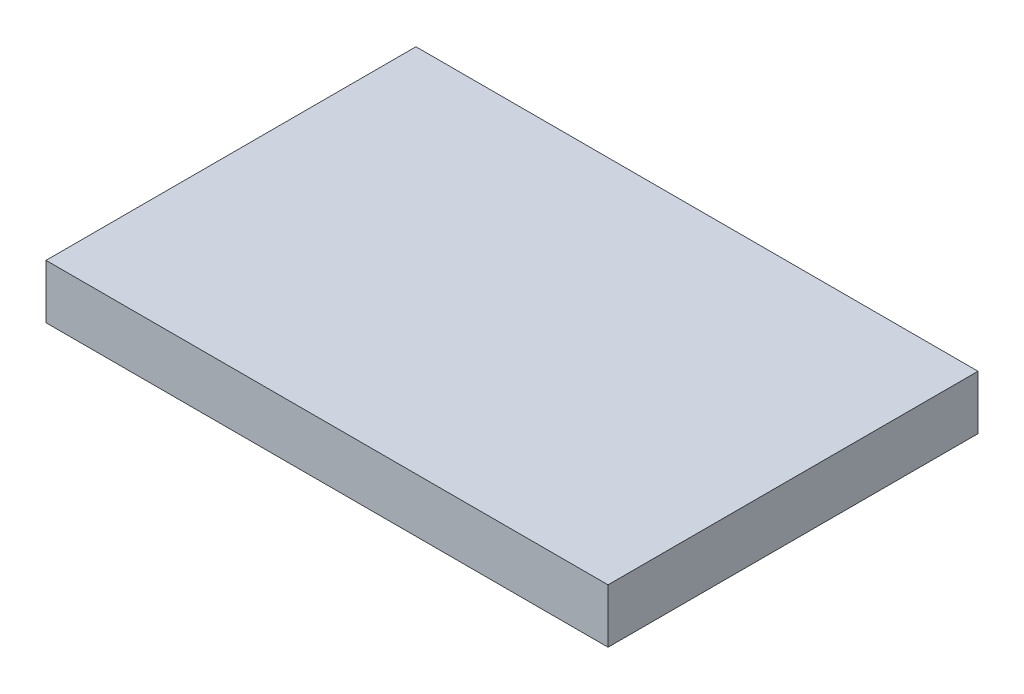
SolidWorks part; units mm, degrees
ref_plane "Front Plane" through (0, 0, 0) normal (0, 0, 1) x (1, 0, 0)
ref_plane "Top Plane" through (0, 0, 0) normal (0, 1, 0) x (1, 0, 0)
ref_plane "Right Plane" through (0, 0, 0) normal (1, 0, 0) x (0, 0, -1)
sketch "Sketch1" plane through (0, 0, 0) normal (0, 1, 0) x (1, 0, 0)
  line L1 (-197.5, 130) -> (197.5, 130)
  line L2 (-197.5, 130) -> (-197.5, -130)
  line L3 (-197.5, -130) -> (197.5, -130)
  line L4 (197.5, 130) -> (197.5, -130)
  line L5 (-197.5, 130) -> (197.5, -130) construction
  line L6 (-197.5, -130) -> (197.5, 130) construction
  point P0 (0, 0)
extrude "Boss-Extrude1" add sketch "Sketch1" along normal blind 38
